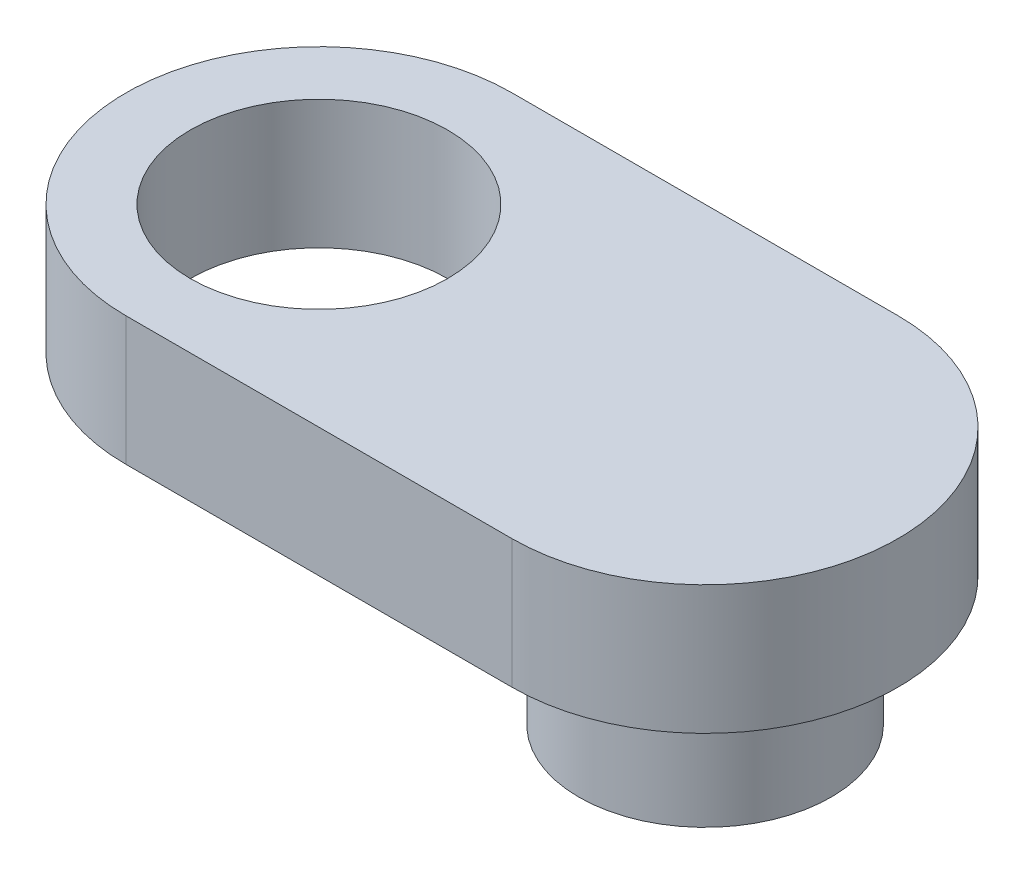
SolidWorks part; units mm, degrees
ref_plane "Front Plane" through (0, 0, 0) normal (0, 0, 1) x (1, 0, 0)
ref_plane "Top Plane" through (0, 0, 0) normal (0, 1, 0) x (1, 0, 0)
ref_plane "Right Plane" through (0, 0, 0) normal (1, 0, 0) x (0, 0, -1)
sketch "Sketch1" plane through (0, 0, 0) normal (0, 1, 0) x (1, 0, 0)
  line L0 (0, 0) -> (15, 0)
  line L1 (0, 0) -> (0, 15) construction
  line L2 (0, 15) -> (15, 15)
  line L3 (15, 0) -> (15, 15) construction
  arc A0 (0, 15) -> (0, 0) centre (0, 7.5) ccw
  arc A1 (15, 0) -> (15, 15) centre (15, 7.5) ccw
  circle A2 centre (0, 7.5) radius 5
  circle A3 centre (15, 7.5) radius 5
  dimension "D3" = 10
  dimension "D4" = 10
  dimension "D1" = 15
  dimension "D2" = 15
extrude "Boss-Extrude1" add sketch "Sketch1" along normal blind 5
sketch "Sketch2" plane through (0, 5, 0) normal (0, 1, 0) x (1, 0, 0)
  circle A0 centre (15, 7.5) radius 4.9
  circle A1 centre (15, 7.5) radius 5 construction
  dimension "D1" = 0
  dimension "D2" = 9.8
extrude "Boss-Extrude2" add sketch "Sketch2" against normal blind 10
sketch "Sketch4" plane through (0, 5, 0) normal (0, 1, 0) x (-1, 0, 0)
  circle A0 centre (-15, -7.5) radius 5
  circle A1 centre (-15, -7.5) radius 4.9 construction
  dimension "D1" = 0
  dimension "D2" = 10
extrude "Boss-Extrude3" add sketch "Sketch4" against normal blind 1
